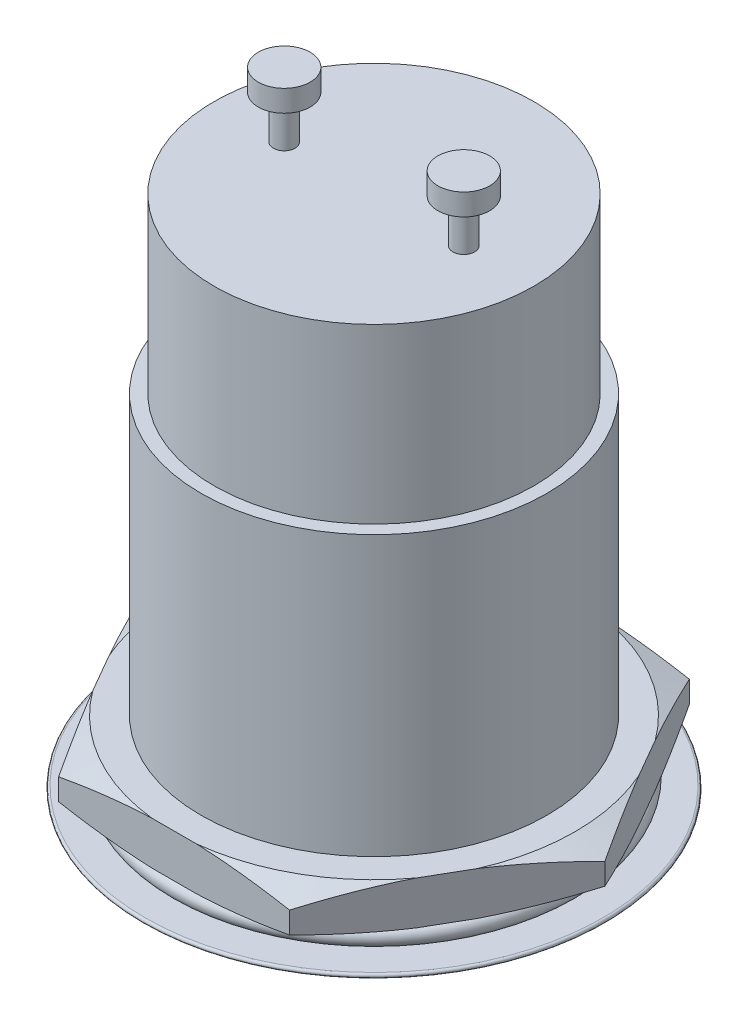
SolidWorks part; units mm, degrees
ref_plane "前视基准面" through (0, 0, 0) normal (0, 0, 1) x (1, 0, 0)
ref_plane "上视基准面" through (0, 0, 0) normal (0, 1, 0) x (1, 0, 0)
ref_plane "右视基准面" through (0, 0, 0) normal (1, 0, 0) x (0, 0, -1)
other "Configuration Table"
sketch "草图1" plane through (0, 0, 0) normal (0, 1, 0) x (1, 0, 0)
  line L1 (10.681, 0) -> (5.3405, 9.25)
  line L2 (5.3405, 9.25) -> (-5.3405, 9.25)
  line L3 (-5.3405, 9.25) -> (-10.681, 0)
  line L4 (-10.681, 0) -> (-5.3405, -9.25)
  line L5 (-5.3405, -9.25) -> (5.3405, -9.25)
  line L6 (5.3405, -9.25) -> (10.681, 0)
  circle A0 centre (0, 0) radius 9.25 construction
  circle A1 centre (0, 0) radius 10.681
  dimension "D1" = 18.5
sketch "草图2" plane through (0, 0, 0) normal (0, 1, 0) x (1, 0, 0)
  circle A0 centre (0, 0) radius 8
  dimension "D1" = 16
extrude "凸台-拉伸1" add sketch "草图2" along normal blind 22.9
sketch "草图4" plane through (0, 0, 0) normal (0, -1, 0) x (1, 0, 0)
  circle A0 centre (0, 0) radius 10.681
extrude "凸台-拉伸3" add sketch "草图4" against normal blind 2
chamfer "倒角1" distance 0.5 angle 70 1 edges at (0, 0, -10.681)
chamfer "倒角2" distance 0.5 angle 70 1 edges at (0, 2, -10.681)
extrude "切除-拉伸1" cut sketch "草图1" along normal blind 2 contours L1 A1 | L2 A1 | L6 A1 | L5 A1 | L4 A1 | L3 A1
sketch "草图6" plane through (0, 0, 0) normal (0, 0, 1) x (1, 0, 0)
  line L0 (0, 0) -> (9, 0)
  line L1 (0, 0) -> (0, -0.8)
  line L2 (0, -0.8) -> (9, -0.8)
  arc A0 (9, -0.8) -> (9, 0) centre (9, -0.4) ccw
  dimension "D1" = 0.8
  dimension "D2" = 9
  dimension "D3" = 9
revolve "旋转1" add sketch "草图6" angle 360 about L1
sketch "草图7" plane through (0, 0, 0) normal (0, 0, 1) x (1, 0, 0)
  line L0 (0, -0.8) -> (10.6, -0.8)
  line L1 (-9, -0.8) -> (9, -0.8) construction
  line L2 (10.6471, -0.9882) -> (8.4412, -2.1647)
  line L3 (7.5, -2.4) -> (0, -2.4)
  line L4 (0, -2.4) -> (0, -0.8)
  arc A0 (10.6, -0.8) -> (10.6471, -0.9882) centre (10.6, -0.9) cw
  arc A1 (8.4412, -2.1647) -> (7.5, -2.4) centre (7.5, -0.4) cw
  point P9 (11, -0.8)
  point P12 (8, -2.4)
  dimension "D4" = 0.1
  dimension "D5" = 2
  dimension "D1" = 1.6
  dimension "D2" = 8
  dimension "D3" = 11
revolve "旋转2" add sketch "草图7" angle 360 about L4
sketch "草图8" plane through (0, -2.4, 0) normal (0, -1, 0) x (1, 0, 0)
  line L0 (0, 0) -> (0, 6) construction
  line L1 (0, 2.1691) -> (0, 5.1691) construction
  line L2 (-0.5, 2.1691) -> (-0.5, 5.1691)
  line L3 (0.5, 2.1691) -> (0.5, 5.1691)
  arc A0 (-4.3636, 4.1181) -> (4.3636, 4.1181) centre (0, 0) ccw
  arc A1 (-3.6364, 3.4317) -> (3.6364, 3.4317) centre (0, 0) ccw
  arc A2 (4.3636, 4.1181) -> (3.6364, 3.4317) centre (4, 3.7749) ccw
  arc A3 (-4.3636, 4.1181) -> (-3.6364, 3.4317) centre (-4, 3.7749) cw
  arc A4 (-0.5, 2.1691) -> (0.5, 2.1691) centre (0, 2.1691) ccw
  arc A5 (0.5, 5.1691) -> (-0.5, 5.1691) centre (0, 5.1691) ccw
  point P9 (0, 3.6691)
  dimension "D1" = 12
  dimension "D2" = 10
  dimension "D3" = 1
  dimension "D5" = 0.5
  dimension "D4" = 4
  dimension "D6" = 3
extrude "切除-拉伸2" cut sketch "草图8" against normal blind 0.1
sketch "草图9" plane through (0, 0, 0) normal (0, 0, 1) x (1, 0, 0)
  line L0 (0, 0) -> (0, 22.9) construction
  line L1 (-1.0307, 0) -> (1.0307, 0) construction
  line L2 (8, 22.9) -> (-8, 22.9) construction
  line L3 (8, 22.9) -> (7.4, 22.9)
  line L4 (7.4, 22.9) -> (7.4, 14.9)
  line L5 (7.4, 14.9) -> (8, 14.9)
  line L6 (8, 2) -> (8, 22.9) construction
  line L7 (8, 14.9) -> (8, 22.9)
  dimension "D1" = 7.4
  dimension "D2" = 8
revolve "切除-旋转1" cut sketch "草图9" angle 360 about L0
sketch "草图10" plane through (0, 0, 0) normal (0, 0, 1) x (1, 0, 0)
  line L0 (4.1539, 22.9) -> (4.6539, 22.9)
  line L1 (7.4, 22.9) -> (-7.4, 22.9) construction
  line L2 (4.6539, 22.9) -> (4.6539, 24.9)
  line L3 (4.6539, 24.9) -> (5.3539, 24.9)
  line L4 (5.3539, 24.9) -> (5.3539, 25.9)
  line L5 (4.1539, 22.9) -> (4.1539, 25.9) construction
  line L6 (5.3539, 25.9) -> (4.1539, 25.9)
  line L7 (4.1539, 22.9) -> (4.1539, 25.9)
  dimension "D1" = 3
  dimension "D2" = 1
  dimension "D3" = 0.5
  dimension "D4" = 1.2
revolve "旋转4" add sketch "草图10" angle 360 about L5
mirror "镜向1" about plane through (0, 0, 0) normal (1, 0, 0) of "旋转4"
